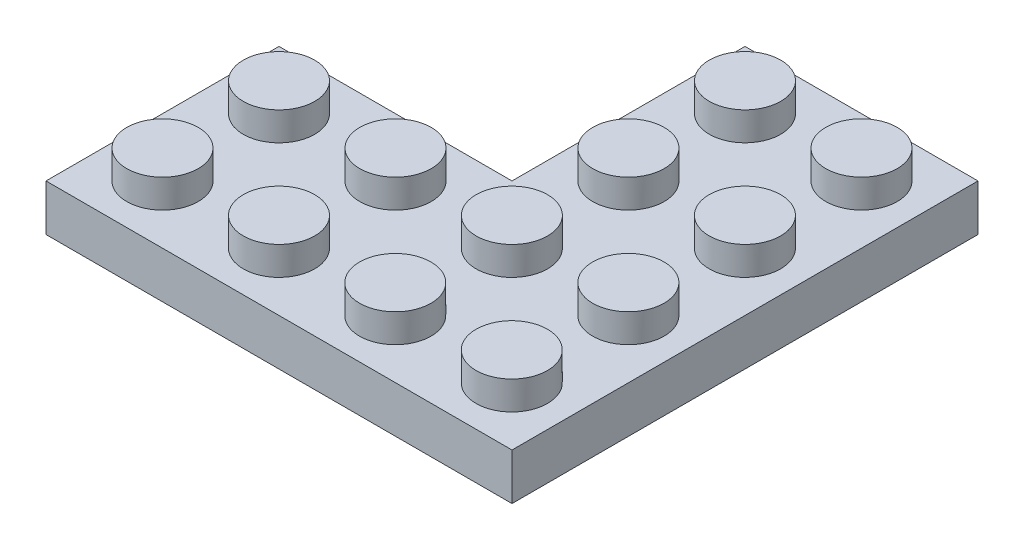
SolidWorks part; units mm, degrees
ref_plane "Front Plane" through (0, 0, 0) normal (0, 0, 1) x (1, 0, 0)
ref_plane "Top Plane" through (0, 0, 0) normal (0, 1, 0) x (1, 0, 0)
ref_plane "Right Plane" through (0, 0, 0) normal (1, 0, 0) x (0, 0, -1)
sketch "Sketch2" plane through (0, 0, 0) normal (0, 1, 0) x (1, 0, 0)
  line L0 (0, 0) -> (-15.91, 0)
  line L1 (-15.91, 0) -> (-15.91, -15.91)
  line L2 (-15.91, -15.91) -> (15.91, -15.91)
  line L3 (15.91, -15.91) -> (15.91, 15.91)
  line L4 (15.91, 15.91) -> (0, 15.91)
  line L5 (0, 15.91) -> (0, 0)
  dimension "D1" = 31.82
  dimension "D2" = 15.91
extrude "Boss-Extrude1" add sketch "Sketch2" against normal blind 3.17
sketch "Sketch3" plane through (0, 0, 0) normal (0, 1, 0) x (1, 0, 0)
  line L1 (15.91, -15.91) -> (15.91, 15.91) construction
  line L2 (15.91, 15.91) -> (0, 15.91) construction
  line L3 (0, 0) -> (-15.91, 0) construction
  line L4 (-15.91, 0) -> (-15.91, -15.91) construction
  line L5 (-15.91, -15.91) -> (15.91, -15.91) construction
  circle A0 centre (11.9325, 11.9325) radius 2.44
  circle A1 centre (11.9325, 3.9725) radius 2.44
  circle A2 centre (11.9325, -3.9875) radius 2.44
  circle A3 centre (11.9325, -11.9475) radius 2.44
  circle A4 centre (3.9775, 3.9725) radius 2.44
  circle A5 centre (3.9775, -3.9875) radius 2.44
  circle A6 centre (3.9775, -11.9475) radius 2.44
  circle A7 centre (3.9775, 11.9325) radius 2.44
  circle A8 centre (-11.93, -3.98) radius 2.44
  circle A9 centre (-3.975, -3.98) radius 2.44
  circle A10 centre (-3.975, -11.935) radius 2.44
  circle A11 centre (-11.93, -11.935) radius 2.44
  dimension "D1" = 3.9775
  dimension "D2" = 4.88
  dimension "D6" = 7.96
  dimension "D7" = 7.955
  dimension "D8" = 3.9775
  dimension "D9" = 4.88
  dimension "D10" = 3.98
  dimension "D14" = 3.98
  dimension "D16" = 7.955
  dimension "D3" = 3.9775
  dimension "D11" = 3.98
  dimension "D15" = 3.975
  dimension "D4" = 4
  dimension "D5" = 2
  dimension "D12" = 2
  dimension "D13" = 2
extrude "Boss-Extrude2" add sketch "Sketch3" along normal blind 1.95
shell "Shell1" thickness 1.25
sketch "Sketch4" plane through (0, -1.25, 0) normal (0, -1, 0) x (1, 0, 0)
  line L0 (0, 0) -> (-15.91, 0) construction
  line L1 (-15.91, 0) -> (-15.91, 15.91) construction
  circle A0 centre (-7.955, 7.955) radius 3.15
  circle A1 centre (0.005, 7.955) radius 3.15
  circle A2 centre (7.965, 7.955) radius 3.15
  circle A3 centre (-7.955, 7.955) radius 2.825
  circle A4 centre (0.005, 7.955) radius 2.825
  circle A5 centre (7.965, 7.955) radius 2.825
  circle A6 centre (7.965, -0.005) radius 2.825
  circle A7 centre (7.965, -0.005) radius 3.15
  circle A8 centre (7.965, -7.965) radius 2.825
  circle A9 centre (7.965, -7.965) radius 3.15
  dimension "D1" = 6.3
  dimension "D3" = 7.955
  dimension "D5" = 7.96
  dimension "D6" = 5.65
  dimension "D8" = 7.96
  dimension "D10" = 7.96
  dimension "D2" = 7.955
  dimension "D4" = 3
  dimension "D7" = 3
  dimension "D9" = 3
extrude "Boss-Extrude3" add sketch "Sketch4" along normal blind 1.65
sketch "Sketch5" plane through (0, -1.25, 0) normal (0, -1, 0) x (1, 0, 0)
  line L0 (0, 0) -> (1.8081, 3.5426) construction
  line L1 (1.0077, 3.4152) -> (2.1745, 2.8197)
  line L2 (2.1745, 2.8197) -> (1.25, 1.0083)
  line L4 (1.25, -14.66) -> (1.25, 1.25) construction
  line L5 (1.0077, 3.4152) -> (0.0832, 1.6038)
  point P11 (1.5911, 3.1174)
  dimension "D1" = 0.655
  dimension "D2" = 2.0337
  dimension "D3" = 3.5
